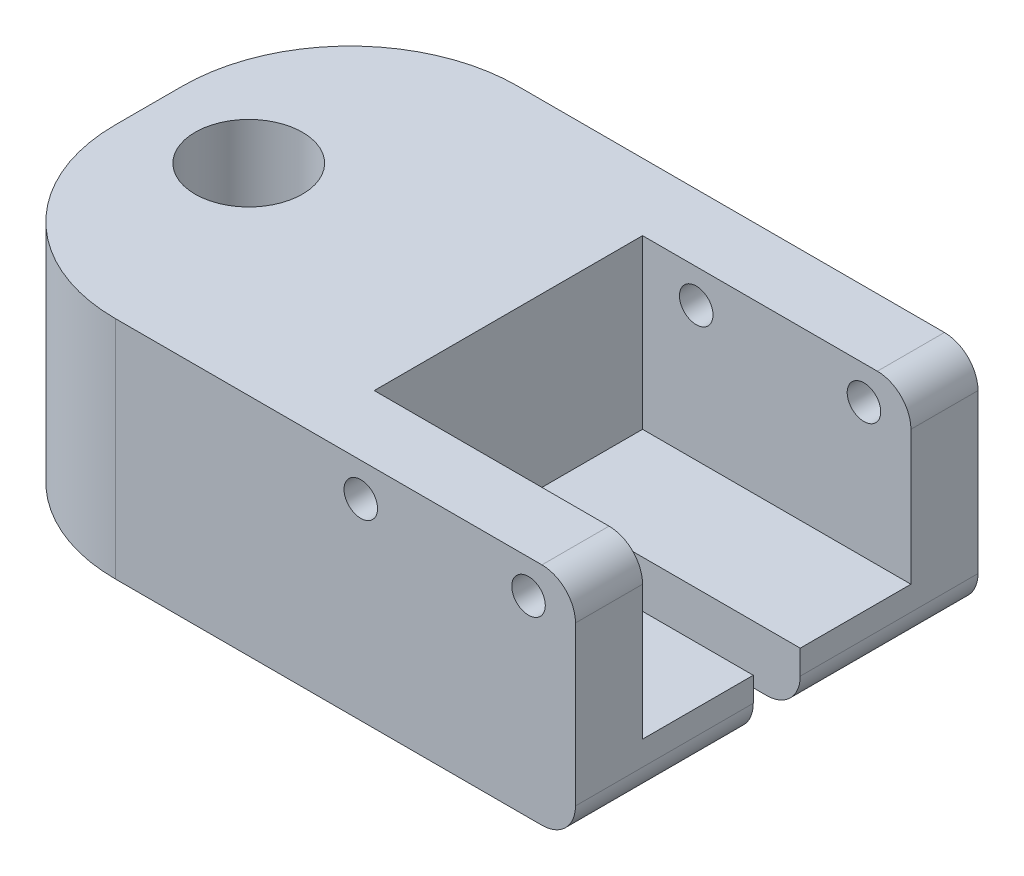
SolidWorks part; units mm, degrees
ref_plane "Front Plane" through (0, 0, 0) normal (0, 0, 1) x (1, 0, 0)
ref_plane "Top Plane" through (0, 0, 0) normal (0, 1, 0) x (1, 0, 0)
ref_plane "Right Plane" through (0, 0, 0) normal (1, 0, 0) x (0, 0, -1)
sketch "Sketch1" plane through (0, 0, 0) normal (0, 0, 1) x (1, 0, 0)
  line L0 (79.3704, 0) -> (79.3704, 33.62)
  line L1 (79.3704, 33.62) -> (-14.2296, 33.62)
  line L2 (-14.2296, 33.62) -> (-14.2296, 0)
  line L3 (-14.2296, 0) -> (79.3704, 0)
extrude "Boss-Extrude2" add sketch "Sketch1" along normal blind 60
sketch "Sketch8" plane through (79.3704, 0, 0) normal (1, 0, 0) x (0, 0, -1)
  line L1 (-60, 33.62) -> (0, 33.62) construction
  line L4 (-30, 8.62) -> (-10, 8.62)
  line L5 (-30, 8.62) -> (-50, 8.62)
  line L6 (-50, 8.62) -> (-50, 33.62)
  line L7 (-50, 33.62) -> (-10, 33.62)
  line L8 (-10, 33.62) -> (-10, 8.62)
extrude "Cut-Extrude2" cut sketch "Sketch8" against normal blind 40
fillet "Fillet2" radius 25 2 edges at (-14.2296, 16.81, 0) (-14.2296, 16.81, 60)
sketch "Sketch9" plane through (0, 33.62, 0) normal (0, 1, 0) x (1, 0, 0)
  point P5 (0.6704, -30)
hole_wizard "Ø16.0 (16) Diameter Hole2" positions "3DSketch3" profile "Sketch10" hole size "Ø16.0" standard "DIN" end condition through all
sketch3d "3DSketch3"
  point P0 (0.6704, 33.62, 30)
sketch "Sketch10" plane through (0.6704, 33.62, 30) normal (1, 0, 0) x (0, 0, 1)
  line L0 (0, 0) -> (0, 33.62)
  line L1 (0, 33.62) -> (8, 33.62)
  line L2 (8, 33.62) -> (8, 0)
  line L5 (8, 0) -> (0, 0)
  line L11 (0, -6.35) -> (0, 107.95) construction
  dimension "Thru Hole Dia." = 16
  dimension "Thru Hole Depth" = 33.62
fillet "Fillet3" radius 5 3 edges at (79.3704, 0, 30) (79.3704, 33.62, 5) (79.3704, 33.62, 55)
sketch "Sketch13" plane through (0, 8.62, 0) normal (0, 1, 0) x (1, 0, 0)
  line L1 (79.3704, -50) -> (79.3704, -10) construction
  line L2 (39.3704, -10) -> (39.3704, -50) construction
  line L5 (79.3704, -33.5) -> (39.3704, -33.5)
  line L6 (39.3704, -33.5) -> (39.3704, -26.5)
  line L7 (39.3704, -26.5) -> (79.3704, -26.5)
  line L8 (79.3704, -26.5) -> (79.3704, -33.5)
extrude "Cut-Extrude3" cut sketch "Sketch13" against normal through all
sketch "Sketch14" plane through (0, 0, 60) normal (0, 0, 1) x (1, 0, 0)
  point P5 (47.3704, 28.62)
  point P6 (72.3704, 28.62)
hole_wizard "Ø5.0 (5) Diameter Hole1" positions "3DSketch4" profile "Sketch15" hole size "Ø5.0" standard "DIN" end condition through all
sketch3d "3DSketch4"
  point P0 (72.3704, 28.62, 60)
  point P3 (47.3704, 28.62, 60)
sketch "Sketch15" plane through (72.3704, 28.62, 60) normal (1, 0, 0) x (0, -1, 0)
  line L0 (0, 0) -> (0, 60)
  line L1 (0, 60) -> (2.5, 60)
  line L2 (2.5, 60) -> (2.5, 0)
  line L5 (2.5, 0) -> (0, 0)
  line L11 (0, -6.35) -> (0, 107.95) construction
  dimension "Thru Hole Dia." = 5
  dimension "Thru Hole Depth" = 60
